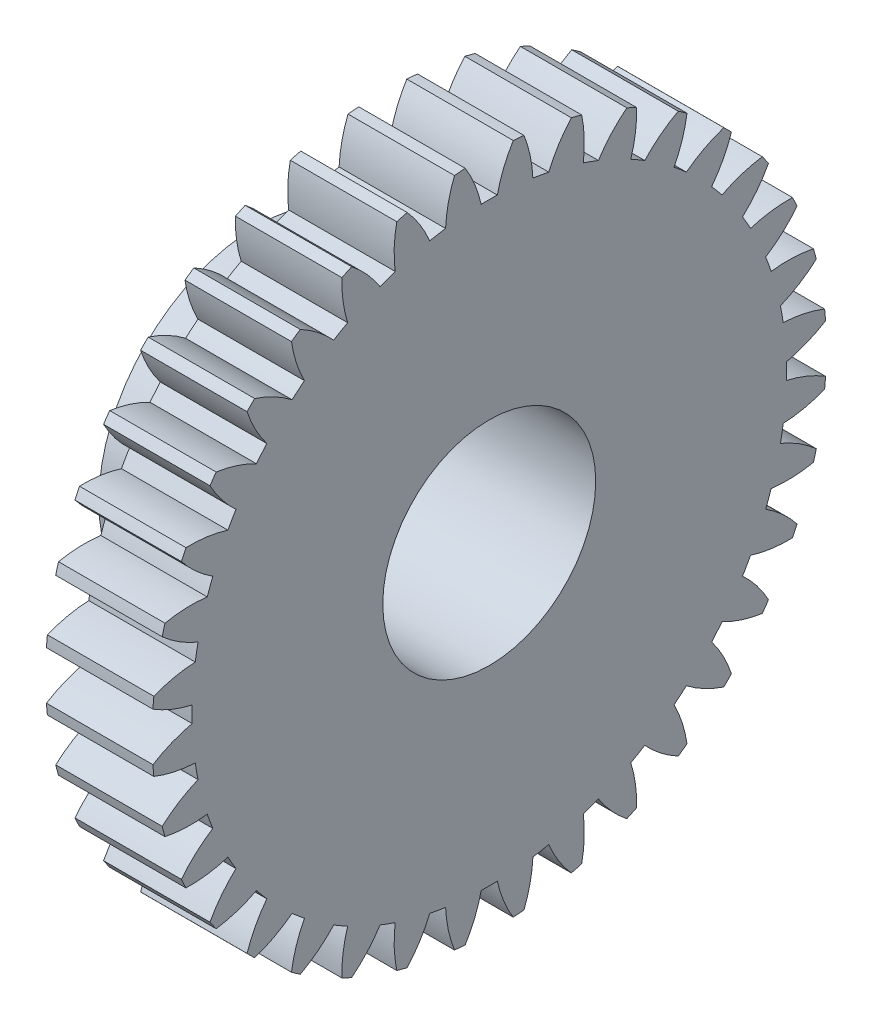
SolidWorks part; units mm, degrees
ref_plane "Plane1" through (0, 0, 0) normal (0, 0, 1) x (1, 0, 0)
ref_plane "Plane2" through (0, 0, 0) normal (0, 1, 0) x (1, 0, 0)
ref_plane "Plane3" through (0, 0, 0) normal (1, 0, 0) x (0, 0, -1)
sketch "HoldingSke" plane through (0, 0, 0) normal (0, 1, 0) x (1, 0, 0)
  line L0 (0, 0) -> (1.618, -1.1756)
  line L1 (-15, 0) -> (100, 0) construction
  line L2 (0, 0) -> (-2.1039, 2.3779)
  line L3 (0, 0) -> (-11.863, 4.5341)
  line L4 (0, 0) -> (6.9867, 5.0761)
  line L5 (0, 0) -> (-6.0902, -2.2715)
  line L6 (0, 0) -> (-2.4869, -1.6779)
  line L7 (-2.1039, 2.3779) -> (-0.7048, 8.7256)
  line L8 (-76.2, 54.61) -> (-75.2, 54.61)
  line L9 (-71.009, 38.7566) -> (-53.1078, 45.2721)
  line L10 (-76.2, 71.12) -> (104.1128, 71.12)
  line L11 (0, 0) -> (-3, 0)
  line L12 (-76.2, 101.6) -> (-76.181, 101.6)
  line L13 (24.9733, 27.94) -> (52.9518, 28.4284)
  line L14 (24.9733, 27.94) -> (24.9743, 27.94)
  line L15 (24.9733, 27.94) -> (100.4006, 29.5858)
  line L16 (-63.627, -0.5) -> (-12.827, -0.5)
  circle A0 centre (0, 0) radius 3
  circle A1 centre (0, 0) radius 4.5
  circle A2 centre (0, 0) radius 4.5
  circle A3 centre (0, 0) radius 3
  dimension "MHD" = 9
  dimension "Hub_dia" = 9
  dimension "Bore" = 6
  dimension "MBD" = 6
  dimension "Num_teeth" = 36
  dimension "Pitch" = 2
  dimension "Overall_len" = 6.5
  dimension "Show_teeth" = 36
  dimension "Thickness" = 3
  dimension "OAL" = 6.5001
  dimension "T_dim" = 1
  dimension "Ap" = 20
  dimension "H" = 19.05
  dimension "Pitch_radius" = 180.3128
  dimension "Width" = 3
  dimension "Backlash" = 0.019
  dimension "Addendum_fac" = 1
  dimension "Dedendum_fac" = 1.25
  dimension "Clearance_fac" = 0.25
  dimension "Dedendum_add" = 0.001
  dimension "Module" = 0.5
sketch "BasProSke" plane through (0, 0, 0) normal (0, 1, 0) x (1, 0, 0)
  line L0 (-10, 0) -> (60, 0) construction
  line L1 (0, 0) -> (0, 9.5)
  line L2 (0, 0) -> (3, 0)
  line L3 (3, 0) -> (3, 9.5)
  line L4 (3, 9.5) -> (0, 9.5)
  dimension "Thickness" = 3
  dimension "Diameter" = 19
revolve "Base-Revolve" add sketch "BasProSke" angle 360 about L0
sketch "TooCutSke" plane through (0, 0, 0) normal (1, 0, 0) x (0, 0, -1)
  line L1 (0, 0) -> (0, 107) construction
  line L2 (0, 0) -> (-0.4258, 8.9899) construction
  line L3 (0, 0) -> (-1.5676, 17.9172) construction
  line L4 (-0.4258, 8.9899) -> (-0.7838, 8.9586) construction
  arc A0 (0.2272, 8.3709) -> (-0.2272, 8.3709) centre (0, 0) ccw
  arc A1 (0.6921, 9.5002) -> (-0.6921, 9.5002) centre (0, 0) ccw
  circle A2 centre (0, 0) radius 9 construction
  circle A3 centre (0, 0) radius 8.4572 construction
  arc A4 (-0.2272, 8.3709) -> (-0.6921, 9.5002) centre (-3.7404, 7.5851) ccw
  arc A5 (0.6921, 9.5002) -> (0.2272, 8.3709) centre (3.7404, 7.5851) ccw
  dimension "Root_dia" = 16.748
  dimension "Overcut_dia" = 19.0508
  dimension "Pitch_dia" = 18
  dimension "Base_dia" = 16.9145
  dimension "Flank_rad" = 3.6
  dimension "Half_ang" = 5
  dimension "Half_CT" = 0.3593
extrude "ToothCut" cut sketch "TooCutSke" along normal through all
fillet "Breaks" [suppressed] radius 0.01
fillet "RootFillets" [suppressed] radius 0.126
pattern_circular "TeethCuts" count 36 over 360 about axis through (0, 0, 0) along (1, 0, 0) of "ToothCut", "RootFillets", "Breaks"
sketch "HubNeaOneSke" plane through (0, 0, 0) normal (-1, 0, 0) x (0, 0, 1)
  circle A0 centre (0, 0) radius 4.5
  dimension "Diameter" = 9
extrude "HubNearOne" add sketch "HubNeaOneSke" along normal blind 3.5001
sketch "HubNeaBotSke" plane through (0, 0, 0) normal (-1, 0, 0) x (0, 0, 1)
  circle A0 centre (0, 0) radius 4.5
  dimension "Diameter" = 9
extrude "HubNearBoth" [suppressed] add sketch "HubNeaBotSke" along normal blind 1.75
ref_plane "FarPln" through (3, 0, 0) normal (1, 0, 0) x (0, 0, -1)
sketch "HubFarSke" plane through (3, 0, 0) normal (1, 0, 0) x (0, 0, -1)
  circle A0 centre (0, 0) radius 4.5
  dimension "Diameter" = 9
extrude "HubFar" [suppressed] add sketch "HubFarSke" along normal blind 1.75
sketch "BorSke" plane through (0, 0, 0) normal (1, 0, 0) x (0, 0, -1)
  circle A0 centre (0, 0) radius 3
  dimension "Diameter" = 6
extrude "Bore" cut sketch "BorSke" along normal mid plane 13.0001
sketch "KeySke" plane through (0, 0, 0) normal (1, 0, 0) x (0, 0, -1)
  line L0 (-1, 0) -> (-1, 4)
  line L1 (-1, 4) -> (1, 4)
  line L2 (1, 4) -> (1, 0)
  line L3 (0, 0) -> (0, 34) construction
  line L4 (-1, 0) -> (1, 0)
  dimension "Offset" = 4
  dimension "Width" = 2
extrude "Keyway" [suppressed] cut sketch "KeySke" along normal mid plane 13.0001
pattern_circular "Keyway2" [suppressed] count 2 every 90 about axis through (-10, 0, 0) along (1, 0, 0)
sketch "Sketch1" plane through (-3.5001, 0, 0) normal (-1, 0, 0) x (0, 0, 1)
  line L0 (0, 4.5) -> (0, -4.5) construction
  circle A0 centre (0, 0) radius 4.5 construction
  circle A1 centre (0, 0) radius 4.5 construction
sketch "Sketch2" plane through (3, 0, 0) normal (1, 0, 0) x (0, 0, -1)
  line L0 (0, 4.5) -> (0, -4.5) construction
ref_plane "Plane4" through (0, 0, 0) normal (0, 0, 1) x (1, 0, 0)
sketch "Sketch3" plane through (0, 0, 0) normal (0, 0, 1) x (1, 0, 0)
  line L0 (-3.5001, 4.5) -> (-3.5001, -4.5) construction
  circle A0 centre (-1.7501, 0) radius 1.25
  dimension "D1" = 1.75
  dimension "D2" = 2.5
extrude "Cut-Extrude1" cut sketch "Sketch3" against normal mid plane 10
equation "' \"Module@HoldingSke\" = 6.35"
equation "' \"Num_teeth@HoldingSke\" = 12"
equation "' \"Ap@HoldingSke\" =  20"
equation "' \"Ap@HoldingSke\" = 20"
equation "' \"Width@HoldingSke\" = 0.5 * 25.4"
equation "' \"Hub_dia@HoldingSke\"= 1 * 25.4"
equation "' \"Hub_dia@HoldingSke\" = 1 * 25.4"
equation "' \"Overall_len@HoldingSke\" = 1.0 * 25.4"
equation "' \"Bore@HoldingSke\" = 0.75 * 25.4"
equation "' \"T_dim@HoldingSke\" = 0.1 * 25.4"
equation "' \"Width@KeySke\" = 0.25 * 25.4"
equation "' \"Show_teeth@HoldingSke\" = 13"
equation "' \"Backlash@HoldingSke\" = 0.009 * 25.4"
equation "' \"Addendum_fac@HoldingSke\" = 1.0"
equation "' \"Dedendum_fac@HoldingSke\" = 1.25"
equation "' \"Dedendum_add@HoldingSke\" = 0.00005 * 25.4"
equation "' \"Clearance_fac@HoldingSke\" = 0.25"
equation "\"Pitch@HoldingSke\" = 1 / \"Module@HoldingSke\""
equation "\"Overcut_dia@TooCutSke\" = (\"Num_teeth@HoldingSke\" + 2 * \"Addendum_fac@HoldingSke\") / \"Pitch@HoldingSke\" + 0.002 * 25.4"
equation "\"Pitch_dia@TooCutSke\" = \"Num_teeth@HoldingSke\" / \"Pitch@HoldingSke\""
equation "\"Base_dia@TooCutSke\" = \"Num_teeth@HoldingSke\" / \"Pitch@HoldingSke\" * cos((\"Ap@HoldingSke\"  * 3.14159265 / 180))"
equation "\"Root_dia@TooCutSke\" = (\"Num_teeth@HoldingSke\" + 2) / \"Pitch@HoldingSke\" - 2 * (\"Addendum_fac@HoldingSke\" + \"Dedendum_fac@HoldingSke\") / \"Pitch@HoldingSke\" - \"Dedendum_add@HoldingSke\" * 2"
equation "\"Half_ang@TooCutSke\" = 180 / \"Num_teeth@HoldingSke\""
equation "\"Half_CT@TooCutSke\" = \"Num_teeth@HoldingSke\" / \"Pitch@HoldingSke\" * sin((3.14159265 / 2 / \"Num_teeth@HoldingSke\")) / 2 - 7 * \"Backlash@HoldingSke\" / 4"
equation "\"Flank_rad@TooCutSke\" = \"Num_teeth@HoldingSke\" / \"Pitch@HoldingSke\" / 5"
equation "\"Radius@RootFillets\" = \"Clearance_fac@HoldingSke\" / \"Pitch@HoldingSke\" + \"Dedendum_add@HoldingSke\""
equation "\"Break_rad@Breaks\" = 0.02 / \"Pitch@HoldingSke\""
equation "\"Thickness@HoldingSke\" = \"Width@HoldingSke\""
equation "\"OAL@HoldingSke\" = \"Thickness@HoldingSke\""
equation "\"MHD@HoldingSke\" = (\"Num_teeth@HoldingSke\" + 2) / \"Pitch@HoldingSke\" - 2 * (\"Addendum_fac@HoldingSke\" + \"Dedendum_fac@HoldingSke\")  / \"Pitch@HoldingSke\" - \"Dedendum_add@HoldingSke\" * 2"
equation "\"MBD@HoldingSke\" = (\"Num_teeth@HoldingSke\" + 2) / \"Pitch@HoldingSke\" - 2 * (\"Addendum_fac@HoldingSke\" + \"Dedendum_fac@HoldingSke\")  / \"Pitch@HoldingSke\" - \"Dedendum_add@HoldingSke\" * 2 - 0.002 * 25.4"
equation "\"MHD@HoldingSke\" = ((sgn( \"MHD@HoldingSke\" - \"Hub_dia@HoldingSke\" )-1)*( \"MHD@HoldingSke\" - \"Hub_dia@HoldingSke\" ))/-2+ \"Hub_dia@HoldingSke\""
equation "\"MBD@HoldingSke\" = ((sgn( \"MBD@HoldingSke\" - \"Bore@HoldingSke\" )-1)*( \"MBD@HoldingSke\" - \"Bore@HoldingSke\" ))/-2+ \"Bore@HoldingSke\""
equation "\"OAL@HoldingSke\" = ((sgn( \"OAL@HoldingSke\" - \"Overall_len@HoldingSke\" )+1)*( \"OAL@HoldingSke\" - \"Overall_len@HoldingSke\" ))/2 + \"Overall_len@HoldingSke\" + 0.000002 * 25.4"
equation "\"Num_teeth@TeethCuts\" = int( \"Show_teeth@HoldingSke\" ) + 1"
equation "\"Num_teeth@TeethCuts\" = ((sgn( \"Num_teeth@TeethCuts\" - \"Num_teeth@HoldingSke\" )-1)*( \"Num_teeth@TeethCuts\" - \"Num_teeth@HoldingSke\" ))/-2+ \"Num_teeth@HoldingSke\""
equation "\"Num_teeth@TeethCuts\" = ((sgn( \"Num_teeth@TeethCuts\" - 2.0)+1)*( \"Num_teeth@TeethCuts\" - 2.0))/2 +2.0"
equation "\"Angle@TeethCuts\" = 360.0 / \"Num_teeth@HoldingSke\""
equation "\"Diameter@BasProSke\" = (\"Num_teeth@HoldingSke\" + 2 * \"Addendum_fac@HoldingSke\") / \"Pitch@HoldingSke\""
equation "\"Thickness@BasProSke\"  = \"Thickness@HoldingSke\""
equation "' \"Fillet_rad@BasProSke\" =  \"Thickness@HoldingSke\" * 0.05"
equation "' \"Fillet_rad@BasProSke\" = \"Thickness@HoldingSke\" * 0.05"
equation "\"MHD@HoldingSke\" = ((sgn( \"MHD@HoldingSke\" - \"Root_dia@TooCutSke\" )-1)*( \"MHD@HoldingSke\" - \"Root_dia@TooCutSke\" ))/-2+ \"Root_dia@TooCutSke\""
equation "\"Diameter@HubNeaOneSke\" = \"MHD@HoldingSke\""
equation "\"Length@HubNearOne\" = \"OAL@HoldingSke\" - \"Thickness@BasProSke\""
equation "\"Diameter@HubNeaBotSke\" = \"MHD@HoldingSke\""
equation "\"Length@HubNearBoth\" = ( \"OAL@HoldingSke\" - \"Thickness@BasProSke\" ) / 2.0"
equation "\"Thickness@FarPln\" = \"Thickness@BasProSke\""
equation "\"Diameter@HubFarSke\" = \"MHD@HoldingSke\""
equation "\"Length@HubFar\" = ( \"OAL@HoldingSke\" - \"Thickness@BasProSke\" ) / 2.0"
equation "\"Diameter@BorSke\" = \"MBD@HoldingSke\""
equation "\"D1@Bore\" = \"OAL@HoldingSke\" * 2.0"
equation "\"D1@Keyway\" = \"OAL@HoldingSke\" * 2.0"
equation "\"Offset@KeySke\" = \"T_dim@HoldingSke\" + \"MBD@HoldingSke\" / 2.0"
